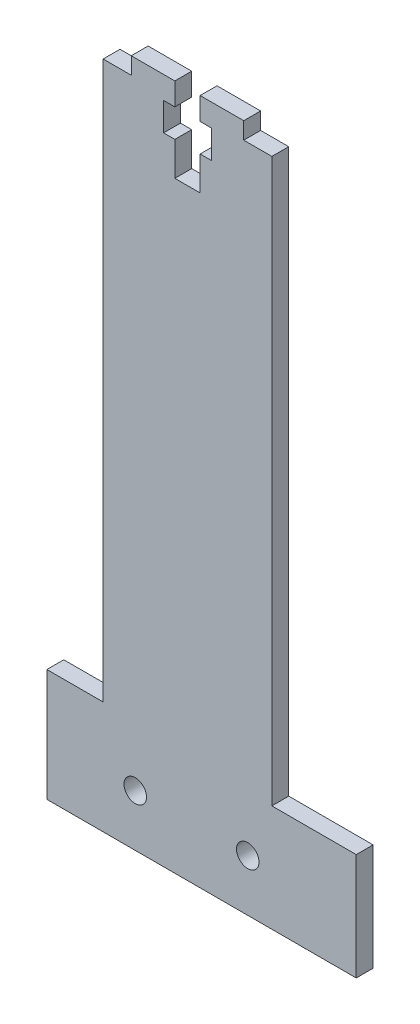
SolidWorks part; units mm, degrees
ref_plane "前视基准面" through (0, 0, 0) normal (0, 0, 1) x (1, 0, 0)
ref_plane "上视基准面" through (0, 0, 0) normal (0, 1, 0) x (1, 0, 0)
ref_plane "右视基准面" through (0, 0, 0) normal (1, 0, 0) x (0, 0, -1)
other "Configuration Table"
sketch "草图1" plane through (0, 0, 0) normal (0, 0, 1) x (1, 0, 0)
  line L0 (-2.25, 62.5) -> (-2.25, 58.5)
  line L1 (-15, 59.5) -> (15, 59.5)
  line L2 (-15, 59.5) -> (-15, -59.5)
  line L3 (-15, -59.5) -> (15, -59.5)
  line L4 (15, 59.5) -> (15, -59.5)
  line L5 (-15, 59.5) -> (15, -59.5) construction
  line L6 (-15, -59.5) -> (15, 59.5) construction
  line L7 (-10, 59.5) -> (10, 59.5)
  line L8 (-10, 59.5) -> (-10, 62.5)
  line L9 (-10, 62.5) -> (10, 62.5)
  line L10 (10, 59.5) -> (10, 62.5)
  line L11 (15, -59.5) -> (30, -59.5)
  line L12 (15, -59.5) -> (15, -40.5)
  line L13 (15, -40.5) -> (30, -40.5)
  line L14 (30, -59.5) -> (30, -40.5)
  line L15 (-15, -59.5) -> (-25, -59.5)
  line L16 (-15, -59.5) -> (-15, -39.5)
  line L17 (-15, -39.5) -> (-25, -39.5)
  line L18 (-25, -59.5) -> (-25, -39.5)
  line L19 (-2.25, 58.5) -> (-4.25, 58.5)
  line L20 (-4.25, 58.5) -> (-4.25, 53.5)
  line L21 (-4.25, 53.5) -> (-2.25, 53.5)
  line L22 (-2.25, 53.5) -> (-2.25, 47.5)
  line L23 (-2.25, 47.5) -> (2.25, 47.5)
  line L24 (2.25, 47.5) -> (2.25, 53.5)
  line L25 (2.25, 53.5) -> (4.25, 53.5)
  line L26 (4.25, 53.5) -> (4.25, 58.5)
  line L27 (4.25, 58.5) -> (2.25, 58.5)
  line L28 (2.25, 58.5) -> (2.25, 62.5)
  point P0 (0, 0)
  point P28 (0, 62.5)
  point P29 (0, 47.5)
  dimension "D1" = 119
  dimension "D2" = 30
  dimension "D3" = 3
  dimension "D4" = 20
  dimension "D5" = 5
  dimension "D6" = 19
  dimension "D7" = 15
  dimension "D8" = 20
  dimension "D9" = 10
  dimension "D10" = 4
  dimension "D11" = 2
  dimension "D12" = 5
  dimension "D13" = 2
  dimension "D14" = 6
  dimension "D15" = 4.5
  dimension "D16" = 6
  dimension "D17" = 2
  dimension "D18" = 5
  dimension "D19" = 2
extrude "凸台-拉伸1" add sketch "草图1" along normal blind 3 contours L18 L15 L2 L17 | L11 L14 L13 L4 | L28 L27 L26 L25 L24 L23 L22 L21 L20 L19 L0 L1 L2 L3 L4 L7 | L28 L7 L10 L9 | L9 L8 L1 L0
sketch "草图2" plane through (0, 0, 3) normal (0, 0, 1) x (1, 0, 0)
  line L0 (-25, -59.5) -> (-25, -39.5) construction
  line L1 (30, -59.5) -> (-25, -59.5) construction
  circle A2 centre (-9.2888, -50.2959) radius 2
  circle A3 centre (10.7112, -50.2959) radius 2
  point P8 (0, 0)
  dimension "D1" = 4
  dimension "D2" = 4
  dimension "D3" = 15.7112
  dimension "D4" = 20
  dimension "D5" = 9.2041
extrude "切除-拉伸1" cut sketch "草图2" against normal through all both and the other way through all
